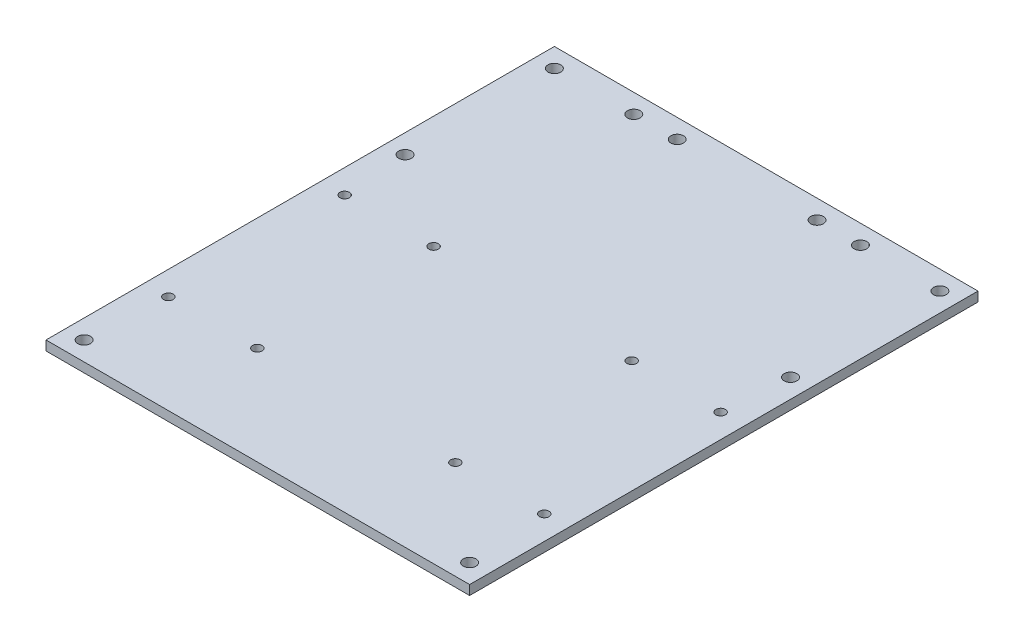
SolidWorks part; units mm, degrees
material "Acrylique (impact moyen-haut)"
ref_plane "Plan de face" through (0, 0, 0) normal (0, 0, 1) x (1, 0, 0)
ref_plane "Plan de dessus" through (0, 0, 0) normal (0, 1, 0) x (1, 0, 0)
ref_plane "Plan de droite" through (0, 0, 0) normal (1, 0, 0) x (0, 0, -1)
sketch "Esquisse1" plane through (0, 0, 0) normal (0, 1, 0) x (1, 0, 0)
  line L1 (-66.665, 80) -> (66.665, 80)
  line L2 (-66.665, 80) -> (-66.665, -80)
  line L3 (-66.665, -80) -> (66.665, -80)
  line L4 (66.665, 80) -> (66.665, -80)
  line L5 (-66.665, 80) -> (66.665, -80) construction
  line L6 (-66.665, -80) -> (66.665, 80) construction
  point P0 (0, 0)
  dimension "D1" = 133.33
  dimension "D2" = 160
extrude "Boss.-Extru.1" add sketch "Esquisse1" along normal blind 3
sketch "Esquisse2" plane through (0, 3, 0) normal (0, 1, 0) x (1, 0, 0)
  line L0 (-60.665, 80) -> (-60.665, 74) construction
  line L1 (66.665, 80) -> (-66.665, 80) construction
  line L2 (-66.665, 74) -> (-60.665, 74) construction
  line L3 (-66.665, 80) -> (-66.665, -80) construction
  line L4 (0, 0) -> (66.665, 0) construction
  line L5 (66.665, -80) -> (66.665, 80) construction
  line L6 (0, 0) -> (0, -80) construction
  line L7 (-66.665, -80) -> (66.665, -80) construction
  circle A0 centre (-60.665, 74) radius 2
  circle A1 centre (60.665, 74) radius 2
  circle A2 centre (60.665, -74) radius 2
  circle A3 centre (-60.665, -74) radius 2
  dimension "D3" = 4
  dimension "D1" = 6
  dimension "D2" = 6
extrude "Enlèv. mat.-Extru.1" cut sketch "Esquisse2" against normal through all
sketch "Esquisse3" plane through (0, 3, 0) normal (0, 1, 0) x (1, 0, 0)
  line L0 (-60.665, 74) -> (-60.665, 27) construction
  line L1 (0, 0) -> (0, 80) construction
  line L2 (66.665, 80) -> (-66.665, 80) construction
  line L3 (-66.665, 80) -> (-66.665, 6.5) construction
  line L4 (-66.665, 80) -> (-66.665, -80) construction
  line L5 (-66.665, 6.5) -> (-59.165, 6.5) construction
  line L6 (-59.165, 6.5) -> (-31.165, 6.5) construction
  line L7 (-59.165, 6.5) -> (-59.165, -49) construction
  circle A0 centre (-60.665, 27) radius 2
  circle A1 centre (60.665, 27) radius 2
  circle A2 centre (-59.165, 6.5) radius 1.5
  circle A3 centre (-31.165, 6.5) radius 1.5
  circle A4 centre (-59.165, -49) radius 1.5
  circle A5 centre (-31.165, -49) radius 1.5
  circle A6 centre (31.165, -49) radius 1.5
  circle A7 centre (59.165, -49) radius 1.5
  circle A8 centre (59.165, 6.5) radius 1.5
  circle A9 centre (31.165, 6.5) radius 1.5
  dimension "D2" = 4
  dimension "D5" = 3
  dimension "D7" = 3
  dimension "D1" = 47
  dimension "D3" = 73.5
  dimension "D4" = 7.5
  dimension "D6" = 28
  dimension "D8" = 55.5
extrude "Enlèv. mat.-Extru.2" cut sketch "Esquisse3" against normal through all
sketch "Esquisse4" plane through (0, 3, 0) normal (0, 1, 0) x (1, 0, 0)
  line L0 (-60.665, 74) -> (-35.665, 74) construction
  line L1 (60.665, 74) -> (35.665, 74) construction
  circle A0 centre (-35.665, 74) radius 2
  circle A3 centre (-60.665, 74) radius 2 construction
  circle A4 centre (35.665, 74) radius 2
  circle A5 centre (60.665, 74) radius 2 construction
  dimension "D2" = 25
  dimension "D1" = 25
extrude "Enlèv. mat.-Extru.3" cut sketch "Esquisse4" against normal blind 3.175
sketch "Esquisse5" plane through (0, 3, 0) normal (0, 1, 0) x (1, 0, 0)
  line L0 (-60.665, 74) -> (60.665, 74) construction
  line L1 (0, 74) -> (-22, 74) construction
  line L2 (0, 74) -> (0, 55.2576) construction
  circle A0 centre (-22, 74) radius 2
  circle A1 centre (-35.665, 74) radius 2 construction
  circle A2 centre (22, 74) radius 2
  dimension "D1" = 22
extrude "Enlèv. mat.-Extru.4" cut sketch "Esquisse5" against normal through all
